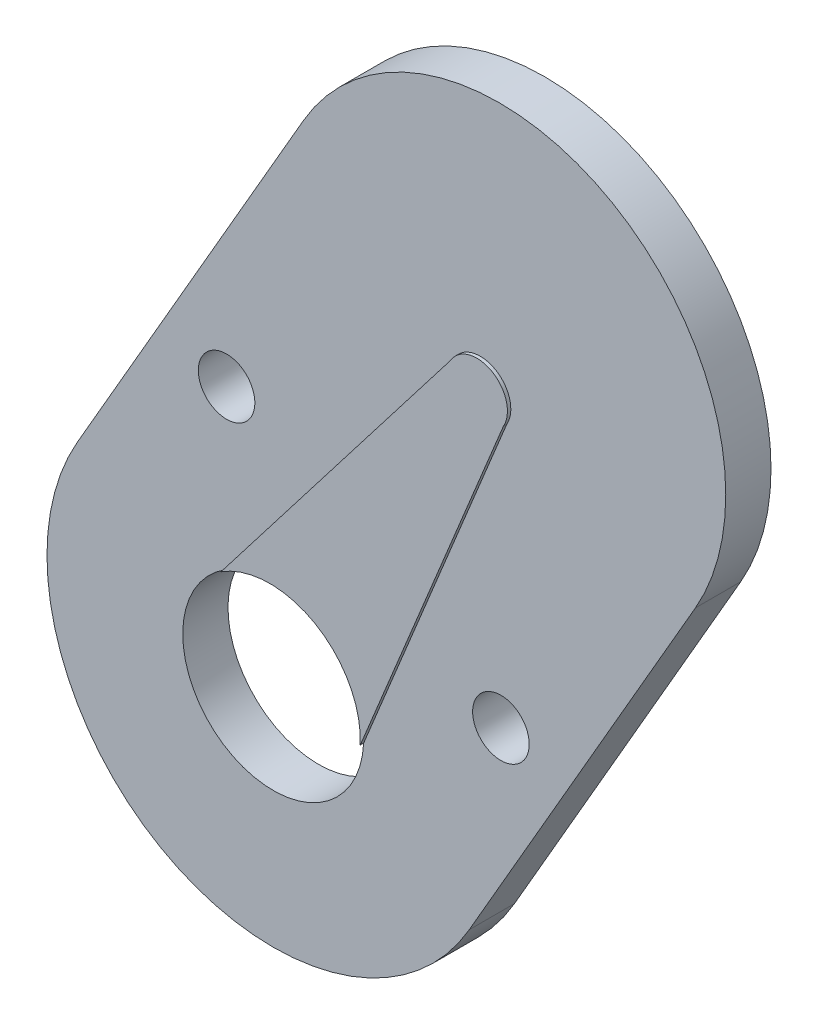
SolidWorks part; units mm, degrees
ref_plane "前视基准面" through (0, 0, 0) normal (0, 0, 1) x (1, 0, 0)
ref_plane "上视基准面" through (0, 0, 0) normal (0, 1, 0) x (1, 0, 0)
ref_plane "右视基准面" through (0, 0, 0) normal (1, 0, 0) x (0, 0, -1)
other "Configuration Table"
sketch "草图1" plane through (0, 0, 0) normal (0, 0, 1) x (1, 0, 0)
  line L0 (8.6603, -5) -> (18.6603, 12.3205)
  line L1 (18.6603, 12.3205) -> (1.3397, 22.3205)
  line L2 (1.3397, 22.3205) -> (-8.6603, 5)
  line L3 (-8.6603, 5) -> (8.6603, -5)
extrude "Retainer_plate_2mm" add sketch "草图1" along normal blind 2 from offset 2
sketch "草图2" plane through (0, 0, 0) normal (0, 0, 1) x (1, 0, 0)
  circle A0 centre (0, 0) radius 10
extrude "Retainer_plate_2mm_root" add sketch "草图2" along normal blind 2 from offset 2
sketch "草图3" plane through (0, 0, 0) normal (0, 0, 1) x (1, 0, 0)
  circle A0 centre (10, 17.3205) radius 10
extrude "Retainer_plate_2mm_tip" add sketch "草图3" along normal blind 2 from offset 2
sketch "草图4" plane through (0, 0, 0) normal (0, 0, 1) x (1, 0, 0)
  line L0 (3.2909, -1.9) -> (10.3191, 15.1733)
  line L1 (10.3191, 15.1733) -> (7.9809, 16.5233)
  line L2 (7.9809, 16.5233) -> (-3.2909, 1.9)
  line L3 (-3.2909, 1.9) -> (3.2909, -1.9)
extrude "Horn_contact_pad_0p15" add sketch "草图4" along normal blind 0.15 from offset 0
sketch "草图5" plane through (0, 0, 0) normal (0, 0, 1) x (1, 0, 0)
  circle A0 centre (0, 0) radius 3.8
extrude "Horn_contact_pad_0p15_root" add sketch "草图5" along normal blind 0.15 from offset 0
sketch "草图6" plane through (0, 0, 0) normal (0, 0, 1) x (1, 0, 0)
  circle A0 centre (9.15, 15.8483) radius 1.35
extrude "Horn_contact_pad_0p15_tip" add sketch "草图6" along normal blind 0.15 from offset 0
sketch "草图7" plane through (0, 0, 0) normal (0, 0, 1) x (1, 0, 0)
  circle A0 centre (0, 0) radius 4
extrude "Boss_clearance_8" cut sketch "草图7" along normal blind 2.5 from offset 2.1
sketch "草图8" plane through (0, 0, 0) normal (0, 0, 1) x (1, 0, 0)
  circle A0 centre (10.0622, 3.4282) radius 1.25
  circle A1 centre (-2.0622, 10.4282) radius 1.25
extrude "M2_clearance_2p5_pitch14" cut sketch "草图8" along normal blind 2.5 from offset 2.1
